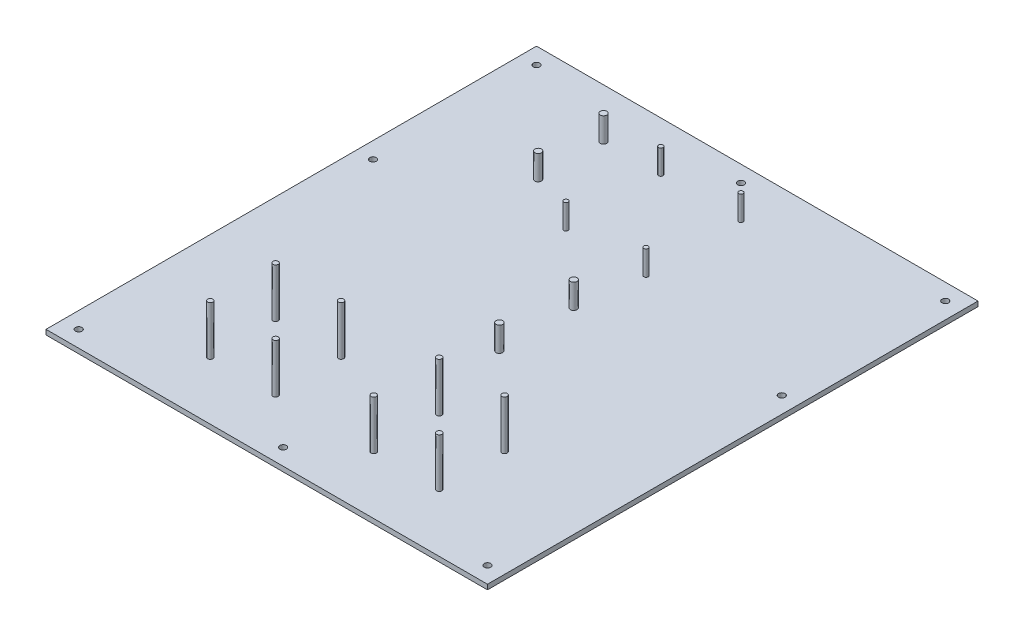
SolidWorks part; units mm, degrees
ref_plane "Front Plane" through (0, 0, 0) normal (0, 0, 1) x (1, 0, 0)
ref_plane "Top Plane" through (0, 0, 0) normal (0, 1, 0) x (1, 0, 0)
ref_plane "Right Plane" through (0, 0, 0) normal (1, 0, 0) x (0, 0, -1)
sketch "Sketch1" plane through (0, 0, 0) normal (0, 1, 0) x (1, 0, 0)
  line L1 (0, 0) -> (270, 0)
  line L2 (0, 0) -> (0, 300)
  line L3 (0, 300) -> (270, 300)
  line L4 (270, 0) -> (270, 300)
  circle A0 centre (10, 290) radius 2
  circle A1 centre (10, 190) radius 2
  circle A2 centre (10, 10) radius 2
  circle A3 centre (135, 10) radius 2
  circle A4 centre (260, 290) radius 2
  circle A5 centre (260, 190) radius 2
  circle A6 centre (260, 10) radius 2
  circle A7 centre (135, 290) radius 2
extrude "Boss-Extrude1" add sketch "Sketch1" along normal blind 3
sketch "Sketch2" plane through (0, 3, 0) normal (0, 1, 0) x (1, 0, 0)
  circle A0 centre (106, 270) radius 1.35
  circle A1 centre (155, 270) radius 1.35
  circle A2 centre (106, 212) radius 1.35
  circle A3 centre (155, 212) radius 1.35
extrude "Boss-Extrude2" add sketch "Sketch2" along normal blind 10
sketch "Sketch3" plane through (0, 3, 0) normal (0, 1, 0) x (1, 0, 0)
  circle A0 centre (150, 172.75) radius 2
  circle A1 centre (150, 127.25) radius 2
extrude "Boss-Extrude3" add sketch "Sketch3" along normal blind 15
sketch "Sketch4" plane through (0, 13, 0) normal (0, 1, 0) x (1, 0, 0)
  circle A0 centre (106, 212) radius 1.35
  circle A1 centre (155, 212) radius 1.35
  circle A2 centre (155, 270) radius 1.35
  circle A3 centre (106, 270) radius 1.35
extrude "Boss-Extrude4" add sketch "Sketch4" along normal blind 5
sketch "Sketch5" plane through (0, 3, 0) normal (0, 1, 0) x (1, 0, 0)
  circle A0 centre (41, 270) radius 2
  circle A1 centre (71, 270) radius 2
extrude "Boss-Extrude5" add sketch "Sketch5" along normal blind 15
sketch "Sketch6" plane through (0, 3, 0) normal (0, 1, 0) x (1, 0, 0)
  circle A0 centre (65, 75.4621) radius 1.6
  circle A1 centre (105, 75.4621) radius 1.6
  circle A2 centre (65, 35.4621) radius 1.6
  circle A3 centre (105, 35.4621) radius 1.6
  circle A4 centre (165, 35.4621) radius 1.6
  circle A5 centre (205, 35.4621) radius 1.6
  circle A6 centre (205, 75.4621) radius 1.6
  circle A7 centre (165, 75.4621) radius 1.6
extrude "Boss-Extrude6" add sketch "Sketch6" along normal blind 15
sketch "Sketch7" plane through (0, 3, 0) normal (0, 1, 0) x (1, 0, 0)
  circle A0 centre (41, 230) radius 2
  circle A1 centre (71, 230) radius 2
extrude "Boss-Extrude7" add sketch "Sketch7" along normal blind 15
sketch "Sketch8" plane through (0, 18, 0) normal (0, 1, 0) x (1, 0, 0)
  circle A0 centre (205, 75.4621) radius 1.6
  circle A1 centre (205, 35.4621) radius 1.6
extrude "Cut-Extrude1" cut sketch "Sketch8" against normal blind 15
sketch "Sketch9" plane through (0, 3, 0) normal (0, 1, 0) x (1, 0, 0)
  circle A0 centre (185, 75.4621) radius 1.6
  circle A1 centre (185, 35.4621) radius 1.6
extrude "Boss-Extrude8" add sketch "Sketch9" along normal blind 15
sketch "Sketch10" plane through (0, 18, 0) normal (0, 1, 0) x (1, 0, 0)
  circle A0 centre (185, 75.4621) radius 1.6
  circle A1 centre (185, 35.4621) radius 1.6
extrude "Cut-Extrude3" cut sketch "Sketch10" against normal blind 15
sketch "Sketch11" plane through (0, 18, 0) normal (0, 1, 0) x (1, 0, 0)
  circle A0 centre (205, 75.4621) radius 1.6
  circle A1 centre (205, 35.4621) radius 1.6
extrude "Boss-Extrude9" add sketch "Sketch11" against normal blind 15
sketch "Sketch12" plane through (0, 18, 0) normal (0, 1, 0) x (1, 0, 0)
  circle A0 centre (65, 35.4621) radius 1.6
  circle A1 centre (105, 35.4621) radius 1.6
  circle A2 centre (105, 75.4621) radius 1.6
  circle A3 centre (65, 75.4621) radius 1.6
  circle A4 centre (165, 75.4621) radius 1.6
  circle A5 centre (165, 35.4621) radius 1.6
  circle A6 centre (205, 35.4621) radius 1.6
  circle A7 centre (205, 75.4621) radius 1.6
extrude "Boss-Extrude10" add sketch "Sketch12" along normal blind 15
sketch "Sketch13" plane through (0, 18, 0) normal (0, 1, 0) x (1, 0, 0)
  circle A0 centre (41, 270) radius 2
  circle A1 centre (41, 230) radius 2
extrude "Cut-Extrude4" cut sketch "Sketch13" against normal blind 15
sketch "Sketch14" plane through (0, 18, 0) normal (0, 1, 0) x (1, 0, 0)
  circle A4 centre (155, 190) radius 1.35
  circle A5 centre (106, 190) radius 1.35
  circle A6 centre (106, 248) radius 1.35
  circle A7 centre (155, 248) radius 1.35
extrude "Boss-Extrude11" add sketch "Sketch14" against normal blind 15
sketch "Sketch15" plane through (0, 18, 0) normal (0, 1, 0) x (1, 0, 0)
  circle A0 centre (106, 212) radius 1.35
  circle A1 centre (155, 212) radius 1.35
  circle A2 centre (155, 270) radius 1.35
  circle A3 centre (106, 270) radius 1.35
extrude "Cut-Extrude7" cut sketch "Sketch15" against normal blind 15
sketch "Sketch16" plane through (0, 18, 0) normal (0, 1, 0) x (1, 0, 0)
  circle A4 centre (106, 270) radius 1.35
  circle A5 centre (155, 270) radius 1.35
  circle A6 centre (106, 212) radius 1.35
  circle A7 centre (155, 212) radius 1.35
extrude "Boss-Extrude12" add sketch "Sketch16" against normal blind 15
sketch "Sketch18" plane through (0, 18, 0) normal (0, 1, 0) x (1, 0, 0)
  circle A0 centre (106, 248) radius 1.35
  circle A1 centre (155, 248) radius 1.35
  circle A2 centre (155, 190) radius 1.35
  circle A3 centre (106, 190) radius 1.35
extrude "Cut-Extrude9" cut sketch "Sketch18" against normal blind 15
